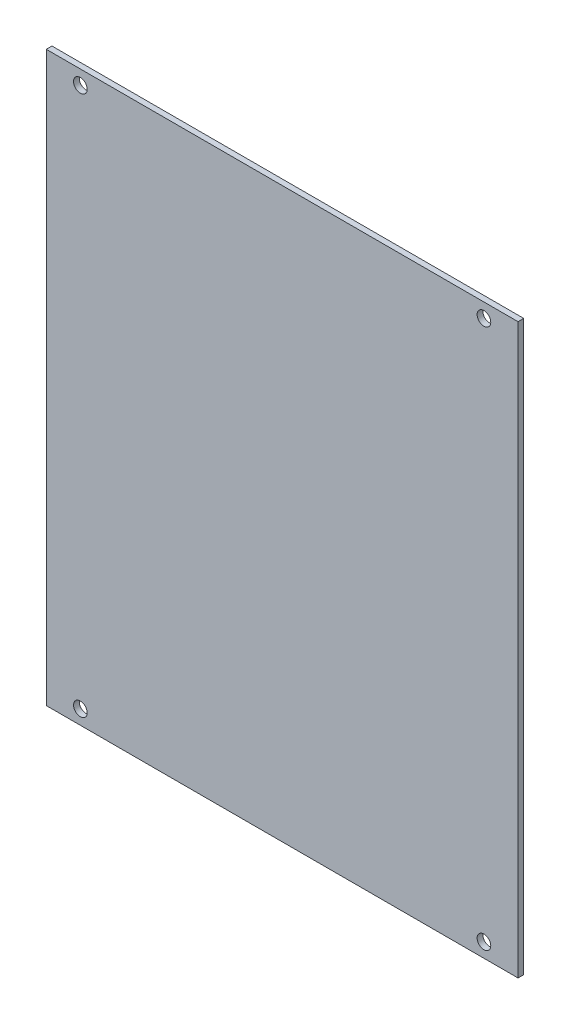
SolidWorks part; units mm, degrees
material "5052-H34"
ref_plane "Frontal" through (0, 0, 0) normal (0, 0, 1) x (1, 0, 0)
ref_plane "Superior" through (0, 0, 0) normal (0, 1, 0) x (1, 0, 0)
ref_plane "Direito" through (0, 0, 0) normal (1, 0, 0) x (0, 0, -1)
sketch "Sketch1" plane through (0, 0, 0) normal (0, 0, 1) x (1, 0, 0)
  line L1 (-41.5, -50) -> (41.5, -50)
  line L2 (-41.5, -50) -> (-41.5, 50)
  line L3 (-41.5, 50) -> (41.5, 50)
  line L4 (41.5, -50) -> (41.5, 50)
  line L5 (-41.5, -50) -> (41.5, 50) construction
  line L6 (-41.5, 50) -> (41.5, -50) construction
  point P0 (0, 0)
  dimension "D1" = 100
  dimension "D2" = 83
extrude "Boss-Extrude1" add sketch "Sketch1" along normal mid plane 1
hole_wizard "M2 Hole1 - A" positions "Sketch3" profile "Sketch2" hole size "M2" standard "DIN" end condition through all
sketch "Sketch3" plane through (0, 0, 0.5) normal (0, 0, 1) x (1, 0, 0)
  line L0 (41.5, 50) -> (-41.5, 50) construction
  line L1 (-41.5, 50) -> (-41.5, -50) construction
  line L2 (41.5, -50) -> (41.5, 50) construction
  line L3 (-41.5, -50) -> (41.5, -50) construction
  point P0 (-35.5, 47.5)
  point P2 (35.5, 47.5)
  point P4 (-35.5, -47.5)
  point P6 (35.5, -47.5)
  point P20 (-35.5, -47.5)
  point P22 (35.5, -47.5)
  dimension "D1" = 2.5
  dimension "D2" = 6
  dimension "D3" = 6
  dimension "D4" = 2.5
  dimension "D5" = 95
sketch "Sketch2" plane through (-35.5, 47.5, 0.5) normal (1, 0, 0) x (0, -1, 0)
  line L0 (0, 0) -> (0, 1)
  line L1 (0, 1) -> (1.2, 1)
  line L2 (1.2, 1) -> (1.2, 0)
  line L5 (1.2, 0) -> (0, 0)
  line L11 (0, -6.35) -> (0, 107.95) construction
  dimension "Thru Hole Dia." = 2.4
  dimension "Thru Hole Depth" = 1
